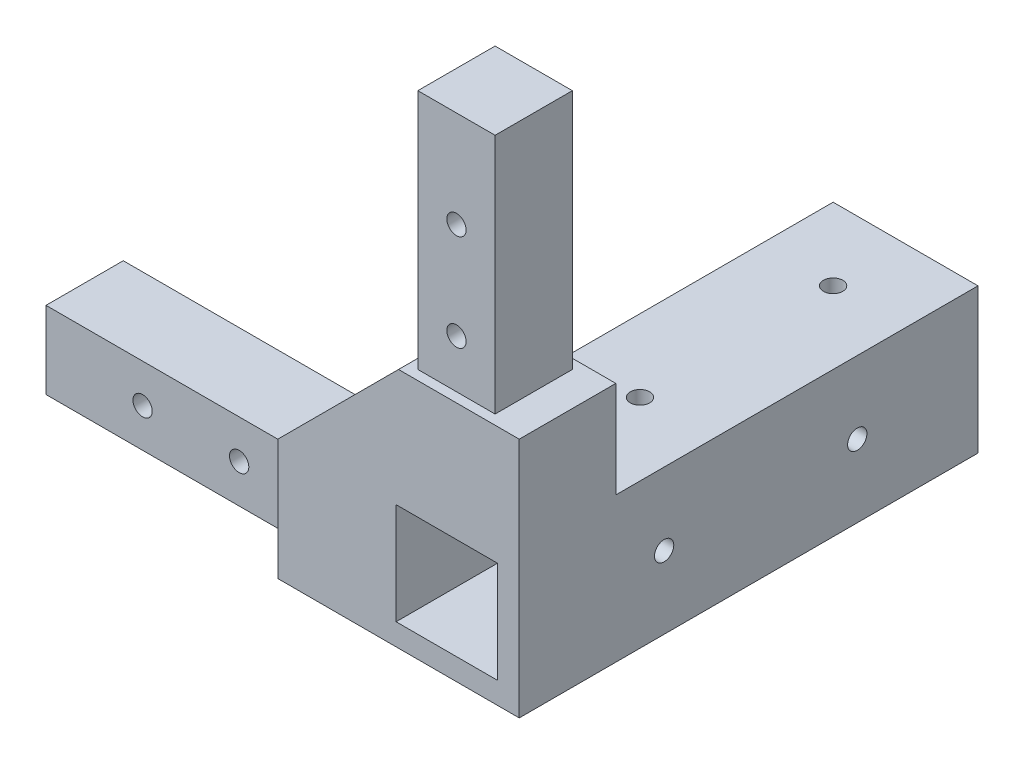
SolidWorks part; units mm, degrees
ref_plane "Front Plane" through (0, 0, 0) normal (0, 0, 1) x (1, 0, 0)
ref_plane "Top Plane" through (0, 0, 0) normal (0, 1, 0) x (1, 0, 0)
ref_plane "Right Plane" through (0, 0, 0) normal (1, 0, 0) x (0, 0, -1)
sketch "Sketch1" plane through (0, 0, 0) normal (0, 0, 1) x (1, 0, 0)
  line L1 (50, -50) -> (-50, -50)
  line L2 (50, -50) -> (50, 50)
  line L3 (50, 50) -> (-50, 50)
  line L4 (-50, -50) -> (-50, 50)
  line L5 (50, -50) -> (-50, 50) construction
  line L6 (50, 50) -> (-50, -50) construction
  point P0 (0, 0)
  dimension "D1" = 100
  dimension "D2" = 100
extrude "Boss-Extrude1" add sketch "Sketch1" against normal blind 100
sketch "Sketch5" plane through (0, 0, -100) normal (0, 0, -1) x (-1, 0, 0)
  line L0 (50, -50) -> (50, 50)
  line L1 (50, 50) -> (-50, 50)
  line L2 (-50, 50) -> (-50, -20)
  line L3 (-50, -50) -> (-50, 50) construction
  line L4 (-20, -20) -> (-50, -20)
  line L5 (50, -50) -> (-20, -50)
  line L8 (-20, -50) -> (-20, -20)
  dimension "D1" = 70
extrude "Cut-Extrude16" cut sketch "Sketch5" against normal blind 70
sketch "Sketch8" plane through (0, 0, -30) normal (0, 0, -1) x (-1, 0, 0)
  line L0 (-20, -20) -> (-20, 50)
  line L1 (50, 50) -> (-50, 50) construction
  line L2 (-20, 50) -> (50, 50)
  line L3 (50, 50) -> (50, -20)
  line L4 (50, -50) -> (50, 50) construction
  line L5 (50, -20) -> (-20, -20)
extrude "Cut-Extrude17" cut sketch "Sketch8" against normal blind 30
sketch "Sketch9" plane through (0, 0, -100) normal (0, 0, -1) x (-1, 0, 0)
  line L3 (-24.5, -45.5) -> (-45.5, -45.5)
  line L4 (-24.5, -45.5) -> (-24.5, -24.5)
  line L5 (-24.5, -24.5) -> (-45.5, -24.5)
  line L6 (-45.5, -45.5) -> (-45.5, -24.5)
  point P8 (-35, -35)
  dimension "D1" = 21
extrude "Cut-Extrude20" cut sketch "Sketch9" against normal blind 100
sketch "Sketch10" plane through (-50, 0, 0) normal (-1, 0, 0) x (0, 0, 1)
  line L3 (-23, -27) -> (-7, -27)
  line L4 (-23, -27) -> (-23, -43)
  line L5 (-23, -43) -> (-7, -43)
  line L6 (-7, -27) -> (-7, -43)
  line L9 (0, -50) -> (-30, -50)
  line L10 (0, -50) -> (0, -20)
  line L11 (0, -20) -> (-30, -20)
  line L12 (-30, -50) -> (-30, -20)
  point P8 (-15, -35)
  point P13 (-15, -35)
  dimension "D1" = 16
extrude "Cut-Extrude21" cut sketch "Sketch10" against normal blind 50
sketch "Sketch11" plane through (0, 0, 0) normal (-1, 0, 0) x (0, 0, 1)
  line L3 (-25, -25) -> (-5, -25)
  line L4 (-25, -25) -> (-25, -45)
  line L5 (-25, -45) -> (-5, -45)
  line L6 (-5, -25) -> (-5, -45)
  line L9 (0, -50) -> (-30, -50)
  line L10 (0, -50) -> (0, -20)
  line L11 (0, -20) -> (-30, -20)
  line L12 (-30, -50) -> (-30, -20)
  point P8 (-15, -35)
  point P13 (-15, -35)
  dimension "D1" = 20
extrude "Cut-Extrude22" cut sketch "Sketch11" against normal blind 20
sketch "Sketch12" plane through (0, 50, 0) normal (0, 1, 0) x (1, 0, 0)
  line L0 (20, 30) -> (50, 0) construction
  line L1 (50, 30) -> (20, 0) construction
  line L3 (25, 25) -> (45, 25)
  line L4 (25, 25) -> (25, 5)
  line L5 (25, 5) -> (45, 5)
  line L6 (45, 25) -> (45, 5)
  line L7 (25, 25) -> (45, 5) construction
  line L8 (25, 5) -> (45, 25) construction
  line L9 (20, 30) -> (50, 30)
  line L10 (20, 30) -> (20, 0)
  line L11 (20, 0) -> (50, 0)
  line L12 (50, 30) -> (50, 0)
  line L13 (20, 30) -> (50, 0) construction
  line L14 (20, 0) -> (50, 30) construction
  point P8 (35, 15)
  point P13 (35, 15)
  dimension "D1" = 20
extrude "Cut-Extrude23" cut sketch "Sketch12" against normal blind 70
sketch "Sketch13" plane through (0, 50, 0) normal (0, 1, 0) x (1, 0, 0)
  line L0 (25, 25) -> (45, 5) construction
  line L1 (45, 25) -> (25, 5) construction
  line L3 (27, 23) -> (43, 23)
  line L4 (27, 23) -> (27, 7)
  line L5 (27, 7) -> (43, 7)
  line L6 (43, 23) -> (43, 7)
  line L7 (27, 23) -> (43, 7) construction
  line L8 (27, 7) -> (43, 23) construction
  line L9 (25, 25) -> (45, 25)
  line L10 (25, 25) -> (25, 5)
  line L11 (25, 5) -> (45, 5)
  line L12 (45, 25) -> (45, 5)
  line L13 (25, 25) -> (45, 5) construction
  line L14 (25, 5) -> (45, 25) construction
  point P8 (35, 15)
  point P13 (35, 15)
  dimension "D1" = 16
extrude "Cut-Extrude24" cut sketch "Sketch13" against normal blind 50
sketch "Sketch15" plane through (0, -20, 0) normal (0, 1, 0) x (1, 0, 0)
  line L0 (35, 100) -> (35, 85) construction
  line L1 (50, 100) -> (20, 100) construction
  line L2 (35, 85) -> (35, 45) construction
  circle A0 centre (35, 85) radius 2
  circle A1 centre (35, 45) radius 2
  dimension "D2" = 40
  dimension "D1" = 15
extrude "Cut-Extrude25" cut sketch "Sketch15" against normal blind 30
sketch "Sketch16" plane through (50, 0, 0) normal (1, 0, 0) x (0, 0, -1)
  circle A0 centre (75, -35) radius 2
  circle A1 centre (35, -35) radius 2
  dimension "D2" = 40
extrude "Cut-Extrude26" cut sketch "Sketch16" against normal blind 30
sketch "Sketch17" plane through (0, 0, -23) normal (0, 0, -1) x (-1, 0, 0)
  line L2 (-35, 30) -> (-35, 10) construction
  circle A0 centre (-35, 30) radius 2
  circle A1 centre (-35, 10) radius 2
  dimension "D2" = 0
extrude "Cut-Extrude27" cut sketch "Sketch17" against normal blind 16
sketch "Sketch18" plane through (0, 0, -23) normal (0, 0, -1) x (-1, 0, 0)
  circle A0 centre (30, -35) radius 2
  circle A1 centre (10, -35) radius 2
  dimension "D2" = 20
extrude "Cut-Extrude29" cut sketch "Sketch18" against normal blind 16
sketch "Sketch19" plane through (0, 0, 0) normal (0, 0, 1) x (1, 0, 0)
  line L0 (20, -20) -> (50, -50) construction
  line L2 (20, -50) -> (50, -50)
  line L3 (20, -50) -> (20, -20)
  line L4 (20, -20) -> (50, -20)
  line L5 (50, -50) -> (50, -20)
  line L6 (20, -50) -> (50, -20) construction
  line L7 (20, -20) -> (50, -50) construction
  point P4 (35, -35)
extrude "Cut-Extrude30" cut sketch "Sketch19" against normal blind 5
sketch "Sketch20" plane through (0, 0, -5) normal (0, 0, 1) x (1, 0, 0)
  line L0 (25, 0) -> (0, -25)
  line L1 (0, -25) -> (0, -27)
  line L2 (0, -45) -> (0, -25) construction
  line L3 (25, 0) -> (27, 0)
  line L4 (25, 0) -> (45, 0) construction
  line L5 (27, 0) -> (27, -27)
  line L6 (27, -27) -> (0, -27)
  dimension "D1" = 2
  dimension "D2" = 2
extrude "Boss-Extrude2" add sketch "Sketch20" against normal blind 20
sketch "Sketch21" plane through (0, 0, 0) normal (-1, 0, 0) x (0, 0, 1)
  line L0 (-23, -43) -> (-25, -43) construction
  line L1 (-25, -25) -> (-25, -45) construction
  line L2 (-25, -43) -> (-25, -50) construction
  line L3 (-7, -43) -> (-5, -43) construction
  line L4 (-5, -45) -> (-5, -25) construction
  line L6 (-5, -43) -> (-25, -43)
  line L7 (-5, -43) -> (-5, -50)
  line L8 (-5, -50) -> (-25, -50)
  line L9 (-25, -43) -> (-25, -50)
  dimension "D1" = 7
extrude "Boss-Extrude6" add sketch "Sketch21" against normal blind 24
sketch "Sketch22" plane through (0, 0, -25) normal (0, 0, -1) x (-1, 0, 0)
  line L0 (-27, -27) -> (-24.5, -24.5) construction
  line L1 (-24.5, -45.5) -> (-24.5, -24.5) construction
  line L2 (-24.5, -24.5) -> (-24.5, -27) construction
  line L3 (-24.5, -45.5) -> (-24.5, -27) construction
  line L4 (-27, -24.5) -> (-24.5, -24.5)
  line L5 (-27, -24.5) -> (-27, -27)
  line L6 (-27, -27) -> (-24.5, -27)
  line L7 (-24.5, -24.5) -> (-24.5, -27)
  line L8 (-27, -24.5) -> (-24.5, -27) construction
  line L9 (-27, -27) -> (-24.5, -24.5) construction
  line L10 (-27, -27) -> (-24.5, -27) construction
  point P7 (-25.75, -25.75)
extrude "Cut-Extrude31" cut sketch "Sketch22" against normal blind 20
sketch "Sketch23" plane through (0, 0, 0) normal (0, 1, 0) x (1, 0, 0)
  line L0 (43, 23) -> (43, 25) construction
  line L1 (45, 25) -> (25, 25) construction
  line L2 (43, 7) -> (43, 5) construction
  line L3 (25, 5) -> (45, 5) construction
  line L4 (43, 5) -> (50, 5) construction
  line L6 (50, 5) -> (43, 5)
  line L7 (50, 5) -> (50, 25)
  line L8 (50, 25) -> (43, 25)
  line L9 (43, 5) -> (43, 25)
  dimension "D1" = 7
extrude "Boss-Extrude7" add sketch "Sketch23" against normal blind 24
